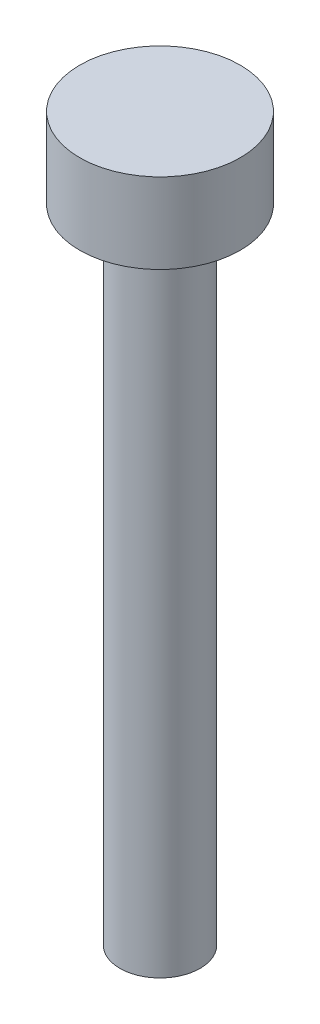
SolidWorks part; units mm, degrees
ref_plane "Front Plane" through (0, 0, 0) normal (0, 0, 1) x (1, 0, 0)
ref_plane "Top Plane" through (0, 0, 0) normal (0, 1, 0) x (1, 0, 0)
ref_plane "Right Plane" through (0, 0, 0) normal (1, 0, 0) x (0, 0, -1)
sketch "Sketch1" plane through (0, 0, 0) normal (0, 1, 0) x (1, 0, 0)
  circle A0 centre (0, 0) radius 3.175
  dimension "D1" = 6.35
extrude "Boss-Extrude1" add sketch "Sketch1" along normal blind 50.8
sketch "Sketch2" plane through (0, 50.8, 0) normal (0, 1, 0) x (1, 0, 0)
  circle A0 centre (0, 0) radius 6.35
  dimension "D1" = 12.7
extrude "Boss-Extrude2" add sketch "Sketch2" along normal blind 6.35
